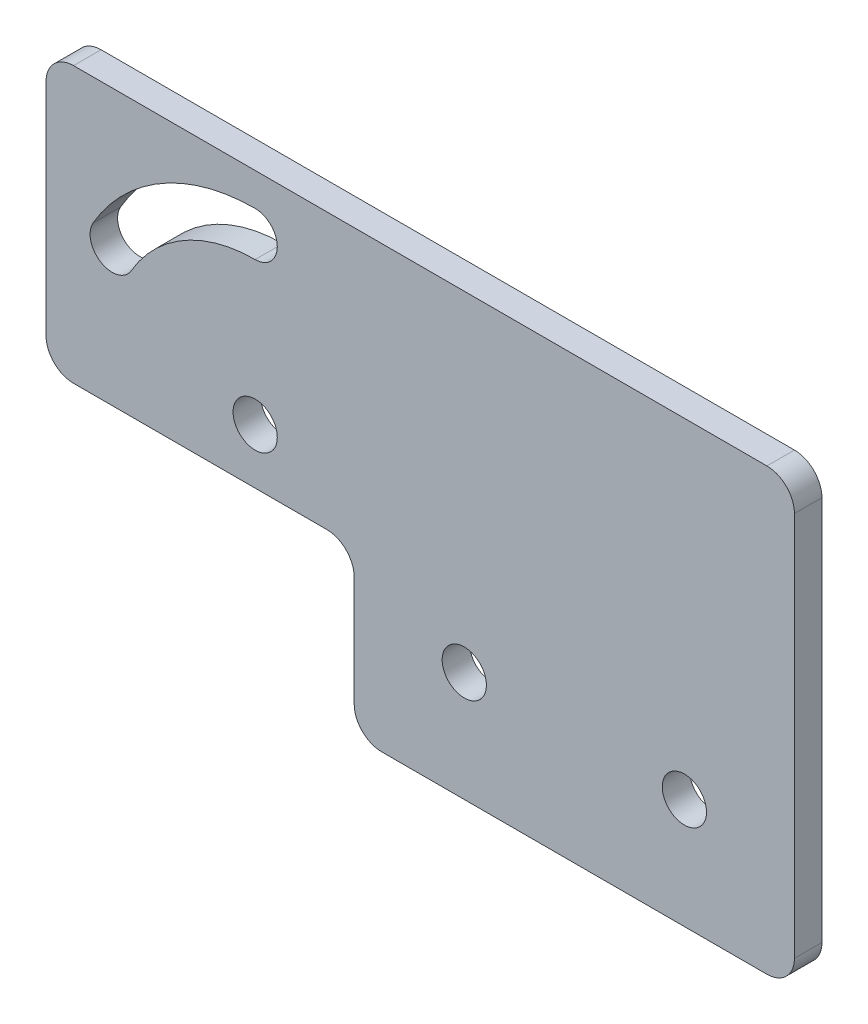
SolidWorks part; units mm, degrees
ref_plane "Front Plane" through (0, 0, 0) normal (0, 0, 1) x (1, 0, 0)
ref_plane "Top Plane" through (0, 0, 0) normal (0, 1, 0) x (1, 0, 0)
ref_plane "Right Plane" through (0, 0, 0) normal (1, 0, 0) x (0, 0, -1)
sketch "Sketch1" plane through (0, 0, 0) normal (0, 0, 1) x (1, 0, 0)
  line L0 (0, 50.8) -> (-35.56, 50.8)
  line L1 (0, 0) -> (50.8, 0)
  line L2 (0, 0) -> (0, 50.8)
  line L3 (0, 50.8) -> (50.8, 50.8)
  line L4 (50.8, 0) -> (50.8, 50.8)
  line L5 (-35.56, 50.8) -> (-35.56, 19.05)
  line L6 (-35.56, 19.05) -> (0, 19.05)
  circle A0 centre (12.7, 12.7) radius 2.5527
  circle A1 centre (38.1, 12.7) radius 2.5527
  circle A2 centre (-11.43, 25.4) radius 2.5527
  arc A19 (-11.43, 44.45) -> (-27.9278, 34.925) centre (-11.43, 25.4) ccw construction
  arc A20 (-30.1385, 36.2013) -> (-11.43, 47.0027) centre (-11.43, 25.4) cw
  arc A21 (-25.7171, 33.6486) -> (-11.43, 41.8973) centre (-11.43, 25.4) cw
  arc A22 (-25.7171, 33.6486) -> (-30.1385, 36.2013) centre (-27.9278, 34.925) cw
  arc A23 (-11.43, 47.0027) -> (-11.43, 41.8973) centre (-11.43, 44.45) cw
  point P14 (0, 0)
  point P15 (-28.93, 35.3744)
  point P45 (-20.955, 41.8978)
  dimension "D3" = 5.1054
  dimension "D11" = 5.1054
  dimension "D10" = 60
  dimension "D1" = 50.8
  dimension "D2" = 50.8
  dimension "D4" = 12.7
  dimension "D5" = 12.7
  dimension "D6" = 25.4
  dimension "D7" = 31.75
  dimension "D8" = 35.56
  dimension "D9" = 6.35
  dimension "D12" = 24.13
  dimension "D14" = 19.05
extrude "Boss-Extrude1" add sketch "Sketch1" along normal blind 3.175
fillet "Fillet1" radius 3.175 6 edges at (0, 0, 1.5875) (0, 19.05, 1.5875) (-35.56, 19.05, 1.5875) (50.8, 50.8, 1.5875) (50.8, 0, 1.5875) (-35.56, 50.8, 1.5875)
